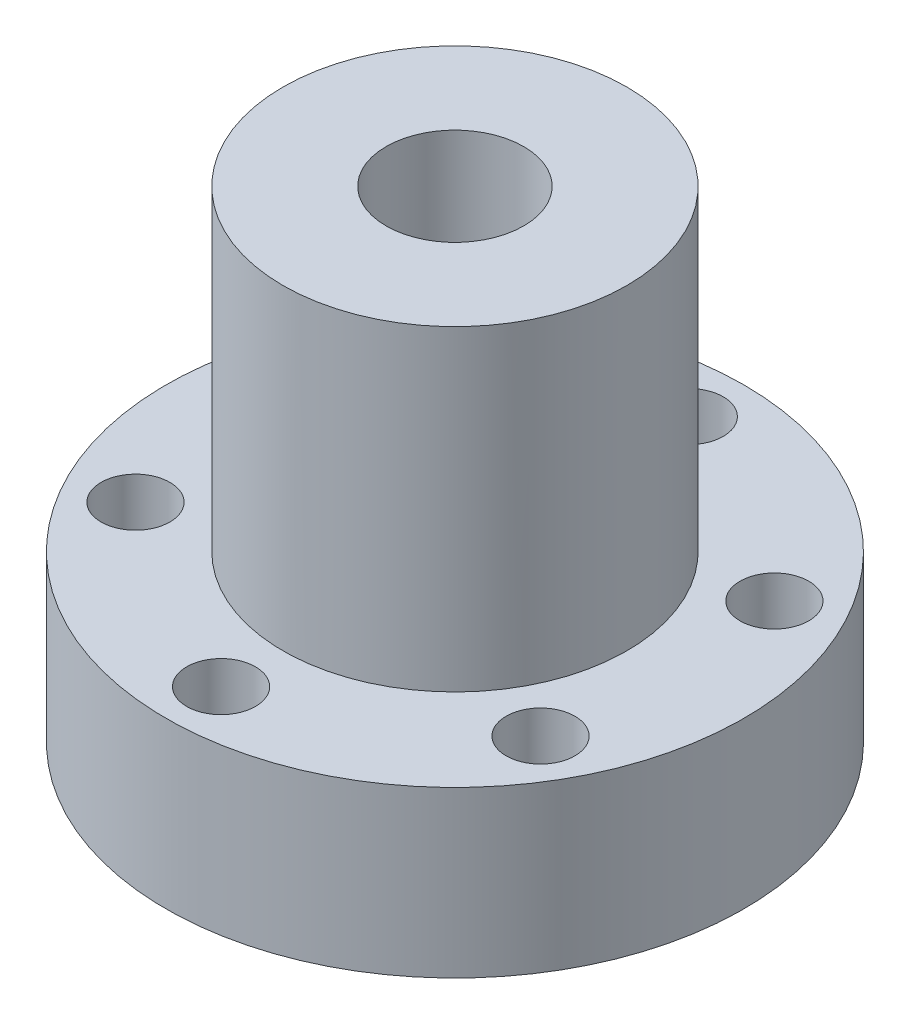
SolidWorks part; units mm, degrees
ref_plane "Front Plane" through (0, 0, 0) normal (0, 0, 1) x (1, 0, 0)
ref_plane "Top Plane" through (0, 0, 0) normal (0, 1, 0) x (1, 0, 0)
ref_plane "Right Plane" through (0, 0, 0) normal (1, 0, 0) x (0, 0, -1)
sketch "Sketch2" plane through (0, 0, 0) normal (0, 1, 0) x (1, 0, 0)
  circle A0 centre (0, 0) radius 5
  circle A1 centre (0, 0) radius 12.5
  dimension "D1" = 25
  dimension "D2" = 10
extrude "Boss-Extrude1" add sketch "Sketch2" along normal blind 23
sketch "Sketch3" plane through (0, 0, 0) normal (0, -1, 0) x (1, 0, 0)
  circle A0 centre (0, 0) radius 21
  circle A1 centre (0, 0) radius 5
  dimension "D1" = 42
  dimension "D2" = 10
extrude "Boss-Extrude2" add sketch "Sketch3" along normal blind 12
sketch "Sketch4" plane through (0, 0, 0) normal (0, 1, 0) x (1, 0, 0)
  circle A1 centre (0, 17) radius 2.5
  circle A2 centre (14.7224, 8.5) radius 2.5
  circle A3 centre (14.7224, -8.5) radius 2.5
  circle A4 centre (0, -17) radius 2.5
  circle A5 centre (-14.7224, -8.5) radius 2.5
  circle A6 centre (-14.7224, 8.5) radius 2.5
  point P17 (0, 0)
  dimension "D1" = 6
  dimension "D3" = 5
  dimension "D2" = 34
extrude "Cut-Extrude1" cut sketch "Sketch4" against normal blind 12
